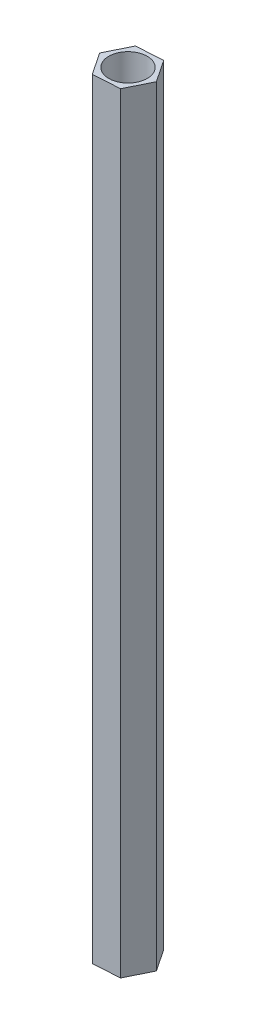
SolidWorks part; units mm, degrees
material "黄铜"
ref_plane "前视基准面" through (0, 0, 0) normal (0, 0, 1) x (1, 0, 0)
ref_plane "上视基准面" through (0, 0, 0) normal (0, 1, 0) x (1, 0, 0)
ref_plane "右视基准面" through (0, 0, 0) normal (1, 0, 0) x (0, 0, -1)
sketch "草图1" plane through (0, 0, 0) normal (0, 1, 0) x (1, 0, 0)
  line L1 (0.9608, -1.4412) -> (1.7285, 0.1115)
  line L2 (1.7285, 0.1115) -> (0.7677, 1.5526)
  line L3 (0.7677, 1.5526) -> (-0.9608, 1.4412)
  line L4 (-0.9608, 1.4412) -> (-1.7285, -0.1115)
  line L5 (-1.7285, -0.1115) -> (-0.7677, -1.5526)
  line L6 (-0.7677, -1.5526) -> (0.9608, -1.4412)
  circle A0 centre (0, 0) radius 1.5 construction
  circle A1 centre (0, 0) radius 1.25
  dimension "D1" = 3
  dimension "D2" = 2.5
extrude "凸台-拉伸1" add sketch "草图1" along normal blind 50
